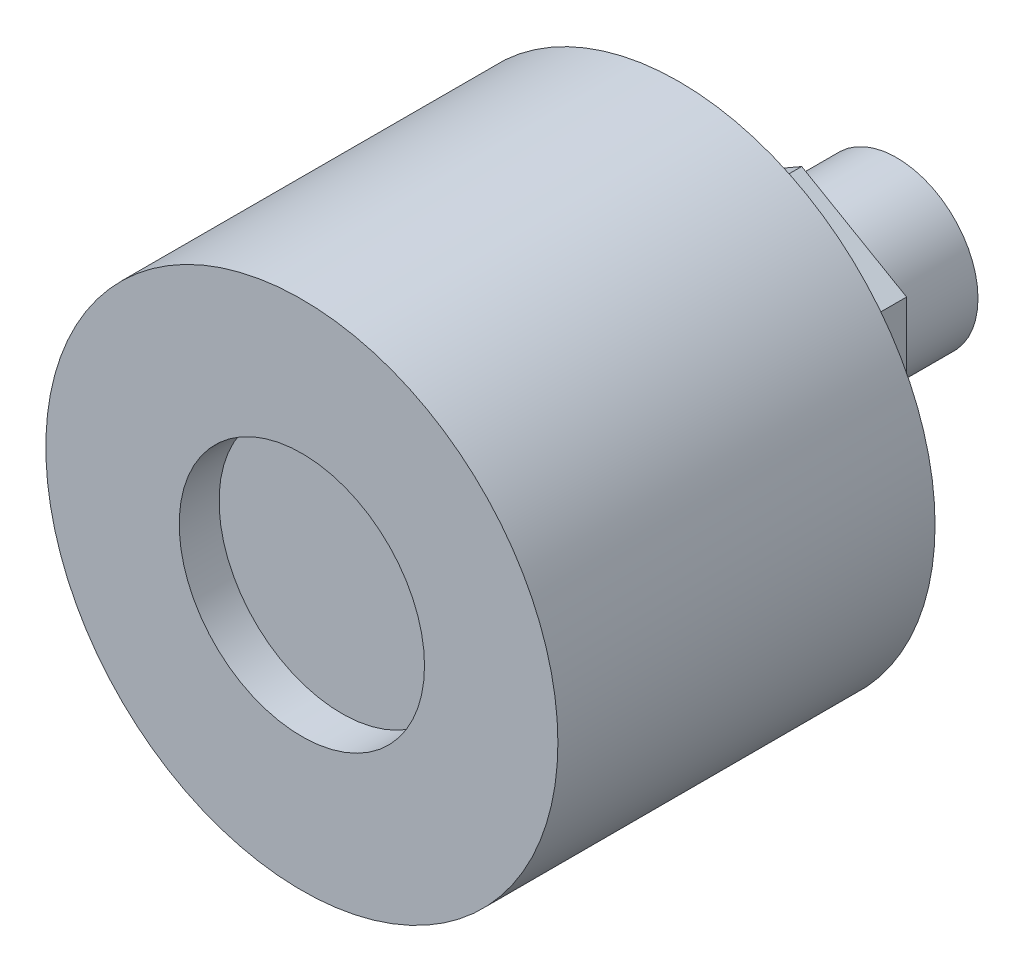
SolidWorks part; units mm, degrees
material "1060 Alloy"
ref_plane "Front Plane" through (0, 0, 0) normal (0, 0, 1) x (1, 0, 0)
ref_plane "Top Plane" through (0, 0, 0) normal (0, 1, 0) x (1, 0, 0)
ref_plane "Right Plane" through (0, 0, 0) normal (1, 0, 0) x (0, 0, -1)
sketch "Sketch3" plane through (0, 0, 0) normal (0, 0, 1) x (1, 0, 0)
  circle A0 centre (0, 0) radius 8.35
  circle A1 centre (0, 0) radius 4
  dimension "D1" = 16.7
extrude "Boss-Extrude1" add sketch "Sketch3" along normal blind 1 and the other way blind 0.3
sketch "Sketch4" plane through (0, 0, -0.3) normal (0, 0, -1) x (-1, 0, 0)
  circle A0 centre (0, 0) radius 8.35
extrude "Boss-Extrude2" add sketch "Sketch4" along normal blind 11
sketch "Sketch5" plane through (0, 0, -11.3) normal (0, 0, -1) x (-1, 0, 0)
  line L0 (0, -3.95) -> (0, 3.95) construction
  line L2 (0, 3.95) -> (-3.4208, 1.975)
  line L3 (-3.4208, 1.975) -> (-3.4208, -1.975)
  line L4 (-3.4208, -1.975) -> (0, -3.95)
  line L5 (0, -3.95) -> (3.4208, -1.975)
  line L6 (3.4208, -1.975) -> (3.4208, 1.975)
  line L7 (3.4208, 1.975) -> (0, 3.95)
  circle A1 centre (0, 0) radius 3.4208 construction
  point P6 (0, 0)
  point P9 (0, 3.95)
  point P13 (0, -3.95)
  dimension "D1" = 7.9
extrude "Boss-Extrude4" add sketch "Sketch5" along normal blind 4
sketch "Sketch6" plane through (0, 0, -15.3) normal (0, 0, -1) x (-1, 0, 0)
  circle A0 centre (0, 0) radius 2.65
  dimension "D1" = 5.3
extrude "Boss-Extrude5" add sketch "Sketch6" along normal blind 3.1
sketch "Sketch7" plane through (0, 0, -18.4) normal (0, 0, -1) x (-1, 0, 0)
  circle A0 centre (0, 0) radius 0.2443
extrude "Cut-Extrude1" cut sketch "Sketch7" against normal blind 2
